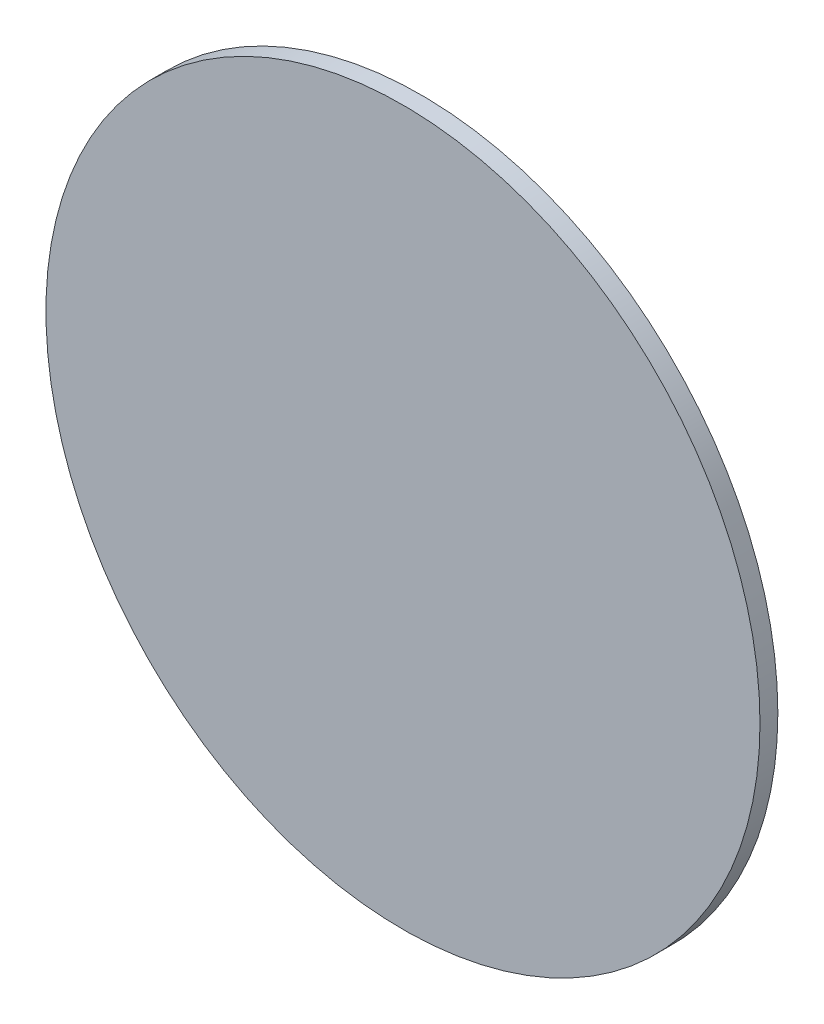
SolidWorks part; units mm, degrees
ref_plane "Спереди" through (0, 0, 0) normal (0, 0, 1) x (1, 0, 0)
ref_plane "Сверху" through (0, 0, 0) normal (0, 1, 0) x (1, 0, 0)
ref_plane "Справа" through (0, 0, 0) normal (1, 0, 0) x (0, 0, -1)
sketch "Эскиз2" plane through (0, 0, 0) normal (0, 1, 0) x (1, 0, 0)
  line L0 (0, 0) -> (60, 0)
  line L1 (60, 0) -> (60, 3)
  line L2 (60, 3) -> (30, 3)
  line L3 (0, 0) -> (0, 33)
  arc A0 (30, 3) -> (0, 33) centre (0, 3) ccw
revolve "Повернуть1" add sketch "Эскиз2" angle 360 about L3
